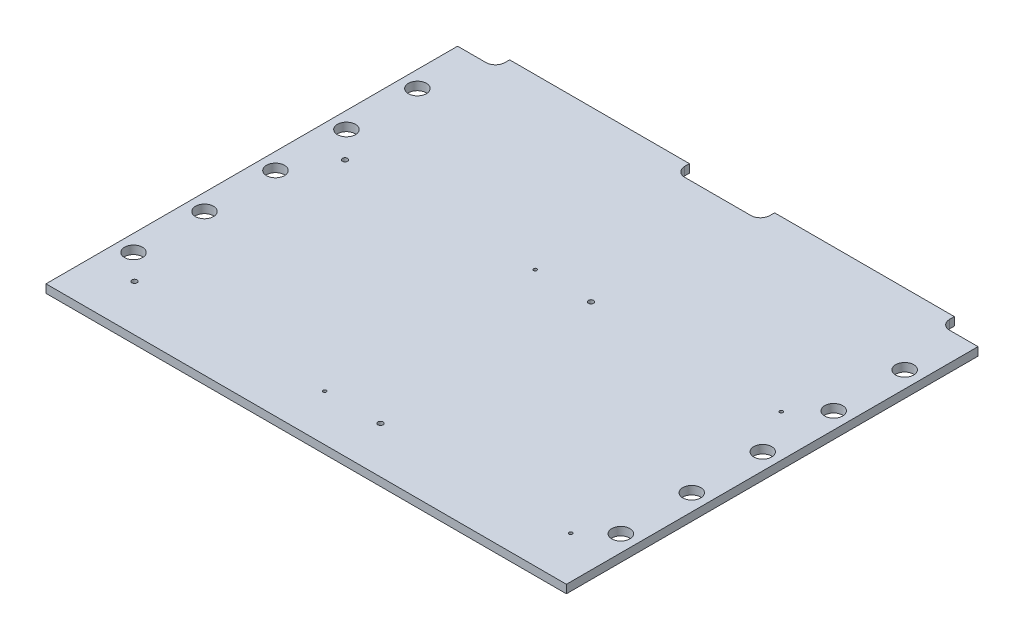
SolidWorks part; units mm, degrees
ref_plane "Front Plane" through (0, 0, 0) normal (0, 0, 1) x (1, 0, 0)
ref_plane "Top Plane" through (0, 0, 0) normal (0, 1, 0) x (1, 0, 0)
ref_plane "Right Plane" through (0, 0, 0) normal (1, 0, 0) x (0, 0, -1)
sketch "Sketch1" plane through (0, 0, 0) normal (0, 1, 0) x (1, 0, 0)
  line L0 (0, 0) -> (110, 0)
  line L1 (110, 0) -> (110, 87)
  line L2 (0, 0) -> (110, 0) construction
  line L3 (0, 0) -> (0, 87)
  line L4 (0, 87) -> (110, 87) construction
  line L5 (0, 90) -> (110, 90) construction
  line L6 (102, 90) -> (102, 89)
  line L7 (0, 0) -> (110, 0) construction
  line L8 (110, 90) -> (110, 0) construction
  line L9 (104, 87) -> (110, 87)
  line L10 (102, 90) -> (64, 90)
  line L11 (48, 87) -> (62, 87)
  line L12 (110, 0) -> (110, 90) construction
  line L13 (110, 90) -> (0, 90) construction
  line L14 (0, 90) -> (0, 0) construction
  line L15 (8, 90) -> (46, 90)
  line L16 (64, 90) -> (64, 89)
  line L18 (0, 87) -> (6, 87)
  line L20 (8, 90) -> (8, 89)
  line L21 (46, 90) -> (46, 89)
  arc A2 (46, 89) -> (48, 87) centre (48, 89) ccw
  arc A3 (102, 89) -> (104, 87) centre (104, 89) ccw
  arc A4 (64, 89) -> (62, 87) centre (62, 89) cw
  arc A8 (8, 89) -> (6, 87) centre (6, 89) cw
extrude "FR4" add sketch "Sketch1" along normal blind 1.7526
ref_plane "center-of-slot" through (0, 0.8763, 0) normal (0, -1, 0) x (-1, 0, 0)
sketch "Sketch7" plane through (0, 1.7526, 0) normal (0, 1, 0) x (1, 0, 0)
  circle A0 centre (3.5, 15) radius 1.905
  circle A1 centre (106.5, 15) radius 1.905
  circle A2 centre (106.5, 30) radius 1.905
  circle A3 centre (106.5, 45) radius 1.905
  circle A4 centre (106.5, 60) radius 1.905
  circle A5 centre (106.5, 75) radius 1.905
  circle A6 centre (3.5, 30) radius 1.905
  circle A7 centre (3.5, 45) radius 1.905
  circle A8 centre (3.5, 60) radius 1.905
  circle A9 centre (3.5, 75) radius 1.905
  dimension "D1" = 2
  dimension "D2" = 5
extrude "Cut-Extrude1" cut sketch "Sketch7" against normal through all
sketch "Sketch8" plane through (0, 1.7526, 0) normal (0, 1, 0) x (1, 0, 0)
  circle A0 centre (8.9, 9.8) radius 0.55
  circle A1 centre (60.9, 9.8) radius 0.55
  circle A2 centre (60.9, 54.3) radius 0.55
  circle A3 centre (8.9, 54.3) radius 0.55
  circle A4 centre (49.1, 9.8) radius 0.35
  circle A5 centre (101.1, 9.8) radius 0.35
  circle A6 centre (101.1, 54.3) radius 0.35
  circle A7 centre (49.1, 54.3) radius 0.35
  dimension "D1" = 2
  dimension "D2" = 2
extrude "controlled-depth-holes.top" cut sketch "Sketch8" against normal blind 1.1176
sketch "Sketch9" plane through (0, 0, 0) normal (0, -1, 0) x (1, 0, 0)
  circle A0 centre (8.9, -9.5) radius 0.55
  circle A1 centre (60.9, -9.5) radius 0.55
  circle A2 centre (60.9, -54) radius 0.55
  circle A3 centre (8.9, -54) radius 0.55
  circle A4 centre (49.1, -9.5) radius 0.35
  circle A5 centre (101.1, -9.5) radius 0.35
  circle A6 centre (101.1, -54) radius 0.35
  circle A7 centre (49.1, -54) radius 0.35
  dimension "D1" = 2
  dimension "D2" = 2
extrude "controlled-depth-holes.bottom" cut sketch "Sketch9" against normal blind 1.1176
